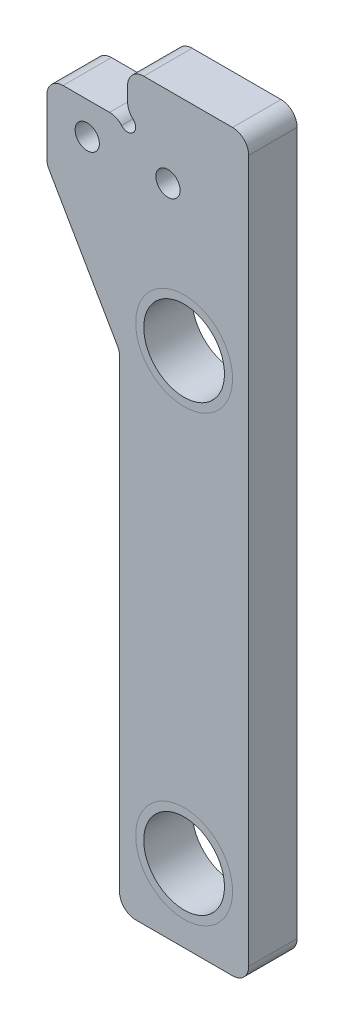
SolidWorks part; units mm, degrees
material "Thornel Mat VMA"
ref_plane "前视基准面" through (0, 0, 0) normal (0, 0, 1) x (1, 0, 0)
ref_plane "上视基准面" through (0, 0, 0) normal (0, 1, 0) x (1, 0, 0)
ref_plane "右视基准面" through (0, 0, 0) normal (1, 0, 0) x (0, 0, -1)
other "Configuration Table"
sketch "草图1" plane through (0, 0, 0) normal (0, 0, 1) x (1, 0, 0)
  line L0 (0, 0) -> (0, -55) construction
  line L1 (8, 20.95) -> (8, -64.05)
  line L2 (8, -64.05) -> (-12, -64.05)
  line L3 (-12, -64.05) -> (-17, -35.6936)
  line L5 (-17, -35.6936) -> (-17, 20.95)
  line L6 (-17, 20.95) -> (8, 20.95)
  line L7 (-2, 16.95) -> (-12, 16.95) construction
  circle A0 centre (0, 0) radius 6
  circle A1 centre (0, -55) radius 6
  circle A2 centre (-2, 16.95) radius 1.5
  circle A3 centre (-12, 16.95) radius 1.5
  dimension "D1" = 12
  dimension "D3" = 10
  dimension "D4" = 3
  dimension "D8" = 20.95
  dimension "D9" = 8
  dimension "D2" = 55
  dimension "D5" = 10
  dimension "D6" = 4
  dimension "D7" = 85
  dimension "D10" = 20
  dimension "D11" = 100
  dimension "D12" = 25
extrude "凸台-拉伸1" add sketch "草图1" along normal blind 6
sketch "草图2" plane through (0, 0, 6) normal (0, 0, 1) x (1, 0, 0)
  circle A0 centre (0, 0) radius 5
  circle A1 centre (0, -55) radius 5
  circle A2 centre (0, -55) radius 6 construction
  circle A3 centre (0, 0) radius 6 construction
  circle A4 centre (0, -55) radius 6
  circle A5 centre (0, 0) radius 6
  dimension "D1" = 10
extrude "凸台-拉伸2" add sketch "草图2" against normal blind 6 separate body
sketch "草图3" plane through (0, 0, 6) normal (0, 0, 1) x (1, 0, 0)
  circle A0 centre (0, 0) radius 8
  circle A1 centre (0, -55) radius 8
  circle A2 centre (0, 0) radius 5 construction
  circle A3 centre (0, -55) radius 5 construction
  circle A4 centre (0, 0) radius 5
  circle A5 centre (0, -55) radius 5
  dimension "D1" = 16
extrude "凸台-拉伸3" add sketch "草图3" along normal blind 0.5 separate body
sketch "草图4" plane through (0, 0, 0) normal (0, 0, -1) x (-1, 0, 0)
  circle A0 centre (0, -55) radius 8 construction
  circle A1 centre (0, -55) radius 5
  circle A2 centre (0, -55) radius 5
  circle A3 centre (0, 0) radius 5
  circle A4 centre (0, 0) radius 5
  circle A5 centre (0, 0) radius 8 construction
  circle A6 centre (0, -55) radius 8
  circle A7 centre (0, 0) radius 8
  dimension "D1" = 0
  dimension "D2" = 0
extrude "凸台-拉伸4" add sketch "草图4" along normal blind 0.5 separate body
sketch "草图5" plane through (0, 0, 0) normal (0, 0, -1) x (-1, 0, 0)
  line L0 (-8, -64.05) -> (-8, 20.95) construction
  line L1 (-8, 20.95) -> (7, 20.95)
  line L2 (-8, 20.95) -> (-8, 26.95)
  line L3 (-8, 26.95) -> (7, 26.95)
  line L4 (7, 20.95) -> (7, 26.95)
  dimension "D1" = 15
  dimension "D2" = 6
extrude "凸台-拉伸5" add sketch "草图5" against normal blind 6
sketch "草图6" plane through (0, 0, 0) normal (0, 0, -1) x (-1, 0, 0)
  circle A0 centre (7, 20.95) radius 1
  dimension "D1" = 2
extrude "切除-拉伸1" cut sketch "草图6" against normal blind 6
sketch "草图9" plane through (0, 0, 6) normal (0, 0, 1) x (1, 0, 0)
  line L0 (-8, -64.05) -> (-8, -4.05)
  line L1 (-12, -64.05) -> (8, -64.05) construction
  line L2 (-8, -4.05) -> (-17, 11.5385)
  line L3 (-17, 20.95) -> (-17, -35.6936) construction
  line L11 (-7, 26.95) -> (-7, 21.95)
  line L12 (-8, 20.95) -> (-17, 20.95)
  line L13 (-17, 20.95) -> (-17, -35.6936)
  line L14 (-17, -35.6936) -> (-12, -64.05)
  line L15 (-12, -64.05) -> (8, -64.05)
  line L16 (8, -64.05) -> (8, 26.95)
  line L17 (8, 26.95) -> (-7, 26.95)
  line L18 (-7, 26.95) -> (-7, 21.95)
  line L19 (-8, 20.95) -> (-17, 20.95)
  line L20 (-17, 20.95) -> (-17, -35.6936)
  line L21 (-17, -35.6936) -> (-12, -64.05)
  line L22 (-12, -64.05) -> (8, -64.05)
  line L23 (8, -64.05) -> (8, 26.95)
  line L24 (8, 26.95) -> (-7, 26.95)
  arc A1 (-8, 20.95) -> (-7, 21.95) centre (-7, 20.95) ccw
  arc A2 (-8, 20.95) -> (-7, 21.95) centre (-7, 20.95) ccw
  line M14 (-17, 20.95) -> (-17, -35.6936)
  line M15 (-17, -35.6936) -> (-12, -64.05)
  line M16 (-12, -64.05) -> (8, -64.05)
  dimension "D2" = 16
  dimension "D3" = 60
  dimension "D4" = 30
  dimension "D1" = 0
extrude "切除-拉伸4" cut sketch "草图9" against normal blind 6 contours L0 L2 M14 M15 M16
fillet "圆角5" radius 2 9 edges at (-17, 11.5385, 3) (-8, 20.95, 3) (-7, 21.95, 3) (-7, 26.95, 3) (8, 26.95, 3) (8, -64.05, 3) (-8, -64.05, 3) (-8, -4.05, 3) (-17, 20.95, 3)
delete or keep bodies "实体-删除/保留 1" type delete bodies bodies 112 111 110 109
